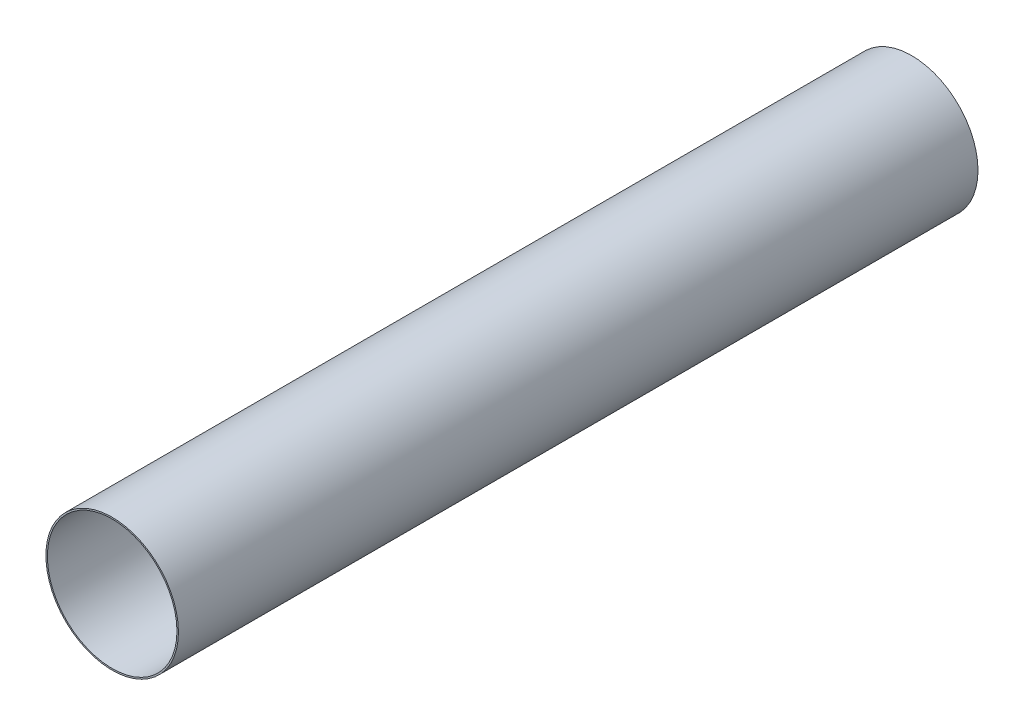
SolidWorks part; units mm, degrees
material "E-Glass Fiber"
ref_plane "Front Plane" through (0, 0, 0) normal (0, 0, 1) x (1, 0, 0)
ref_plane "Top Plane" through (0, 0, 0) normal (0, 1, 0) x (1, 0, 0)
ref_plane "Right Plane" through (0, 0, 0) normal (1, 0, 0) x (0, 0, -1)
sketch "Sketch1" plane through (0, 0, 0) normal (0, 0, 1) x (1, 0, 0)
  circle A0 centre (0, 0) radius 50.8
  circle A1 centre (0, 0) radius 49.6697
  dimension "D1" = 101.6
  dimension "D2" = 99.3394
extrude "Boss-Extrude1" add sketch "Sketch1" along normal blind 612.775
